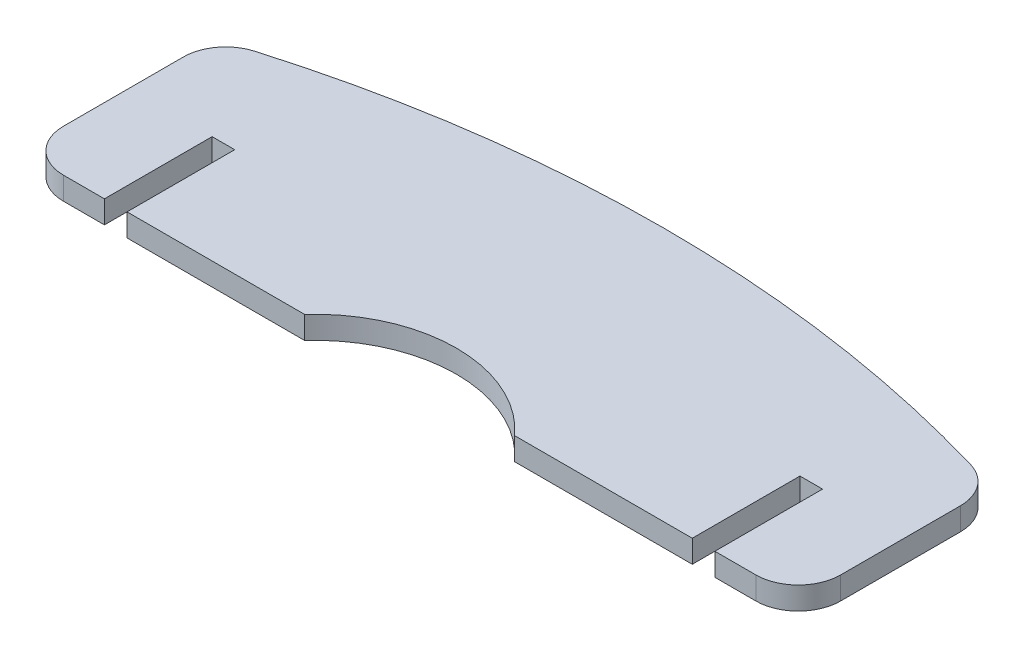
SolidWorks part; units mm, degrees
material "Skleněné vlákno-A"
ref_plane "Přední rovina" through (0, 0, 0) normal (0, 0, 1) x (1, 0, 0)
ref_plane "Horní rovina" through (0, 0, 0) normal (0, 1, 0) x (1, 0, 0)
ref_plane "Pravá rovina" through (0, 0, 0) normal (1, 0, 0) x (0, 0, -1)
sketch "Skica1" plane through (0, 0, 0) normal (0, 1, 0) x (1, 0, 0)
  line L0 (0, 0) -> (0, 85.9523) construction
  line L1 (-27.5, 0) -> (-27.5, -13.6957)
  line L2 (-27.5, -13.6957) -> (27.5, -13.6957)
  line L3 (27.5, 0) -> (27.5, -13.6957)
  arc A0 (-27.5, 0) -> (27.5, 0) centre (0, -85.6957) cw
  dimension "D1" = 55
  dimension "D2" = 18
extrude "Přidat vysunutím1" add sketch "Skica1" along normal mid plane 1.6
sketch "Skica3" plane through (0, 0.8, 0) normal (0, 1, 0) x (1, 0, 0)
  line L1 (-27.5, -2.2166) -> (-27.5, -10.6957)
  line L2 (-24.5, -13.6957) -> (24.5, -13.6957)
  line L3 (-27.5, -13.6957) -> (27.5, -13.6957) construction
  line L5 (0, 0) -> (0, -43.0431) construction
  line L6 (27.5, -13.6957) -> (27.5, 0) construction
  line L7 (27.5, -2.2166) -> (27.5, -10.6957)
  arc A0 (27.5, 0) -> (-27.5, 0) centre (0, -85.6957) ccw construction
  arc A1 (25.3448, 0.6619) -> (-25.3448, 0.6619) centre (0, -85.6957) ccw
  arc A2 (25.3448, 0.6619) -> (27.5, -2.2166) centre (24.5, -2.2166) cw
  arc A3 (24.5, -13.6957) -> (27.5, -10.6957) centre (24.5, -10.6957) ccw
  arc A4 (-24.5, -13.6957) -> (-27.5, -10.6957) centre (-24.5, -10.6957) cw
  arc A5 (-25.3448, 0.6619) -> (-27.5, -2.2166) centre (-24.5, -2.2166) ccw
  point P16 (27.4483, 0.0166)
  dimension "D2" = 3
  dimension "D3" = 3
  dimension "D1" = 3
extrude "Odebrat vysunutím2" cut sketch "Skica3" against normal through all flip side to cut
sketch "Skica2" plane through (0, 0.8, 0) normal (0, 1, 0) x (1, 0, 0)
  line L0 (0, 0) -> (0, 16.8441) construction
  line L1 (-21.6, -6.0757) -> (-20, -6.0757)
  line L2 (-21.6, -6.0757) -> (-21.6, -13.6957)
  line L3 (-21.6, -13.6957) -> (-20, -13.6957)
  line L4 (-20, -6.0757) -> (-20, -13.6957)
  line L5 (20, -6.0757) -> (20, -13.6957)
  line L6 (21.6, -13.6957) -> (20, -13.6957)
  line L7 (21.6, -6.0757) -> (21.6, -13.6957)
  line L8 (21.6, -6.0757) -> (20, -6.0757)
  line L11 (-21.6, -6.0757) -> (-21.6, 1.5443) construction
  line L12 (-24.5, -13.6957) -> (24.5, -13.6957) construction
  dimension "D1" = 1.6
  dimension "D2" = 7.62
  dimension "D3" = 40
extrude "Odebrat vysunutím1" cut sketch "Skica2" against normal through all
sketch "Skica6" plane through (0, 0.8, 0) normal (0, 1, 0) x (1, 0, 0)
  line L0 (-20, -13.6957) -> (20, -13.6957) construction
  arc A0 (-7.4298, -13.6957) -> (7.4298, -13.6957) centre (0, -20.3889) cw
  ellipse E0 centre (0, -20.3889) end of major axis (-7.25, -20.3889) minor radius 7.1697 (7.0931, -18.9055) -> (-7.0931, -18.9055) ccw construction
  dimension "D1" = 10
extrude "Odebrat vysunutím3" cut sketch "Skica6" against normal through all and the other way through all flip side to cut
sketch "Skica4" plane through (0, 0.8, 0) normal (0, 1, 0) x (1, 0, 0)
  line L0 (0, 1.3043) -> (0, 0.8043)
  line L1 (0, 1.3043) -> (-0.5, 1.3043)
  line L3 (5.6856, 1.1183) -> (5.1867, 1.151)
  line L4 (5.6856, 1.1183) -> (5.6529, 0.6194)
  line L5 (11.3469, 0.5612) -> (10.8512, 0.6264)
  line L6 (11.3469, 0.5612) -> (11.2817, 0.0655)
  line L7 (16.9597, -0.3648) -> (16.4693, -0.2673)
  line L8 (16.9597, -0.3648) -> (16.8622, -0.8552)
  line L9 (22.5, -1.6555) -> (22.017, -1.5262)
  line L10 (22.5, -1.6555) -> (22.3707, -2.1385)
  line L11 (-22.5, -1.6555) -> (-22.3707, -2.1385)
  line L12 (-22.5, -1.6555) -> (-22.017, -1.5262)
  line L13 (-16.9597, -0.3648) -> (-16.8622, -0.8552)
  line L14 (-16.9597, -0.3648) -> (-16.4693, -0.2673)
  line L15 (-11.3469, 0.5612) -> (-11.2817, 0.0655)
  line L16 (-11.3469, 0.5612) -> (-10.8512, 0.6264)
  line L17 (-5.6856, 1.1183) -> (-5.6529, 0.6194)
  line L18 (-5.6856, 1.1183) -> (-5.1867, 1.151)
  line L19 (27.5, -10.6957) -> (27.5, -2.2166) construction
  arc A0 (25.3448, 0.6619) -> (-25.3448, 0.6619) centre (0, -85.6957) ccw construction
  arc A1 (0, 1.3043) -> (22.5, -1.6555) centre (0, -85.6957) cw construction
  arc A2 (25.3448, 0.6619) -> (-25.3448, 0.6619) centre (0, -85.6957) ccw construction
  point P3 (0, 4.3043)
  dimension "D1" = 3
  dimension "D2" = 0.5
  dimension "D3" = 5
  dimension "D5" = 5.6887
  dimension "D4" = 5
sketch "Skica5" plane through (0, -0.8, 0) normal (0, 1, 0) x (1, 0, 0)
  line L0 (-20, -7.3345) -> (-18.73, -7.3345)
  line L1 (-20, -13.6957) -> (-20, -6.0757) construction
  line L2 (-20.8, -6.0757) -> (-20.8, -3.0616) construction
  line L3 (-20, -6.0757) -> (-21.6, -6.0757) construction
  line L4 (-21.6, -12.4146) -> (-22.87, -12.4146)
  line L5 (-21.6, -9.8746) -> (-22.87, -9.8746)
  line L6 (-20, -9.8746) -> (-18.73, -9.8746)
  line L7 (-20, -12.4146) -> (-18.73, -12.4146)
  line L8 (-20, -14.9546) -> (-18.73, -14.9546)
  line L9 (-20, -17.4946) -> (-18.73, -17.4946)
  line L10 (-21.6, -7.3345) -> (-22.87, -7.3345)
  line L11 (0, 0) -> (0, -1.7726) construction
  line L12 (21.6, -7.3345) -> (22.87, -7.3345)
  line L13 (20, -12.4146) -> (18.73, -12.4146)
  line L14 (20, -9.8746) -> (18.73, -9.8746)
  line L15 (21.6, -9.8746) -> (22.87, -9.8746)
  line L16 (21.6, -12.4146) -> (22.87, -12.4146)
  line L17 (20, -7.3345) -> (18.73, -7.3345)
  dimension "D2" = 1.27
  dimension "D1" = 3
